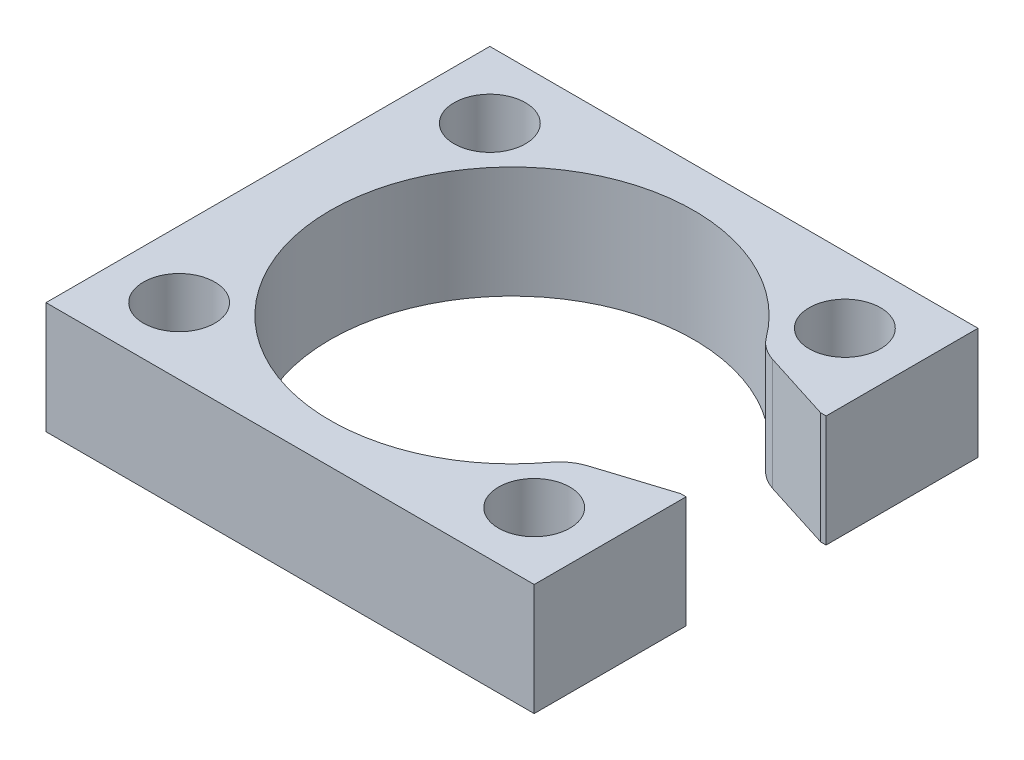
SolidWorks part; units mm, degrees
material "ABS"
ref_plane "Front Plane" through (0, 0, 0) normal (0, 0, 1) x (1, 0, 0)
ref_plane "Top Plane" through (0, 0, 0) normal (0, 1, 0) x (1, 0, 0)
ref_plane "Right Plane" through (0, 0, 0) normal (1, 0, 0) x (0, 0, -1)
sketch "Sketch1" plane through (0, 0, 0) normal (0, 1, 0) x (1, 0, 0)
  line L1 (-17.4625, -15.875) -> (17.4625, -15.875)
  line L2 (-17.4625, -15.875) -> (-17.4625, 15.875)
  line L3 (-17.4625, 15.875) -> (17.4625, 15.875)
  line L4 (17.4625, -15.875) -> (17.4625, 15.875)
  line L5 (-17.4625, -15.875) -> (17.4625, 15.875) construction
  line L6 (-17.4625, 15.875) -> (17.4625, -15.875) construction
  point P0 (0, 0)
  dimension "D1" = 34.925
  dimension "D2" = 31.75
extrude "Plate" add sketch "Sketch1" along normal mid plane 8
hole_wizard "#10 Clearance Hole1" positions "Sketch3" profile "Sketch2" hole size "#10" standard "ANSI Inch" end condition through all
sketch "Sketch3" plane through (0, 4, 0) normal (0, 1, 0) x (1, 0, 0)
  line L12 (12.7, -11.1125) -> (12.7, 11.1125)
  line L13 (12.7, 11.1125) -> (-12.7, 11.1125)
  line L14 (-12.7, 11.1125) -> (-12.7, -11.1125)
  line L15 (-12.7, -11.1125) -> (12.7, -11.1125)
  line L16 (12.7, -11.1125) -> (12.7, 11.1125)
  line L17 (12.7, 11.1125) -> (-12.7, 11.1125)
  line L18 (-12.7, 11.1125) -> (-12.7, -11.1125)
  line L19 (-12.7, -11.1125) -> (12.7, -11.1125)
  point P0 (-12.7, 11.1125)
  point P4 (12.7, 11.1125)
  point P6 (12.7, -11.1125)
  point P10 (-12.7, -11.1125)
  dimension "D1" = 4.7625
sketch "Sketch2" plane through (-12.7, 4, -11.1125) normal (1, 0, 0) x (0, 0, 1)
  line L0 (0, 0) -> (0, 8)
  line L1 (0, 8) -> (2.5527, 8)
  line L2 (2.5527, 8) -> (2.5527, 0)
  line L5 (2.5527, 0) -> (0, 0)
  line L11 (0, -6.35) -> (0, 107.95) construction
  dimension "Thru Hole Dia." = 5.1054
  dimension "Thru Hole Depth" = 8
sketch "Sketch4" plane through (0, 4, 0) normal (0, 1, 0) x (1, 0, 0)
  line L0 (10.6771, 6.5) -> (17, 4.5) construction
  line L1 (17, 4.5) -> (22.225, 4.5) construction
  line L2 (22.225, 4.5) -> (22.225, -4.5) construction
  line L3 (22.225, -4.5) -> (17, -4.5) construction
  line L4 (17, -4.5) -> (10.6771, -6.5) construction
  line L5 (-12.5, 0) -> (17, 0) construction
  line L6 (11.0099, 6.9275) -> (17.0784, 5.008)
  line L7 (17.0784, 5.008) -> (22.733, 5.008)
  line L8 (22.733, 5.008) -> (22.733, -5.008)
  line L9 (22.733, -5.008) -> (17.0784, -5.008)
  line L10 (17.0784, -5.008) -> (11.0099, -6.9275)
  arc A0 (10.6771, 6.5) -> (10.6771, -6.5) centre (0, 0) ccw construction
  arc A1 (11.0099, 6.9275) -> (11.0099, -6.9275) centre (0, 0) ccw
  arc A2 (10.6771, 6.5) -> (10.6771, -6.5) centre (0, 0) ccw construction
  dimension "D1" = 12.5
  dimension "D3" = 13
  dimension "D5" = 29.5
  dimension "D2" = 22.225
  dimension "D4" = 9
  dimension "D6" = 0.508
extrude "Load Cell Cutout" cut sketch "Sketch4" against normal up to next
fillet "Fillet1" radius 3.175 2 edges at (11.0099, 0, 6.9275) (11.0099, 0, -6.9275)
